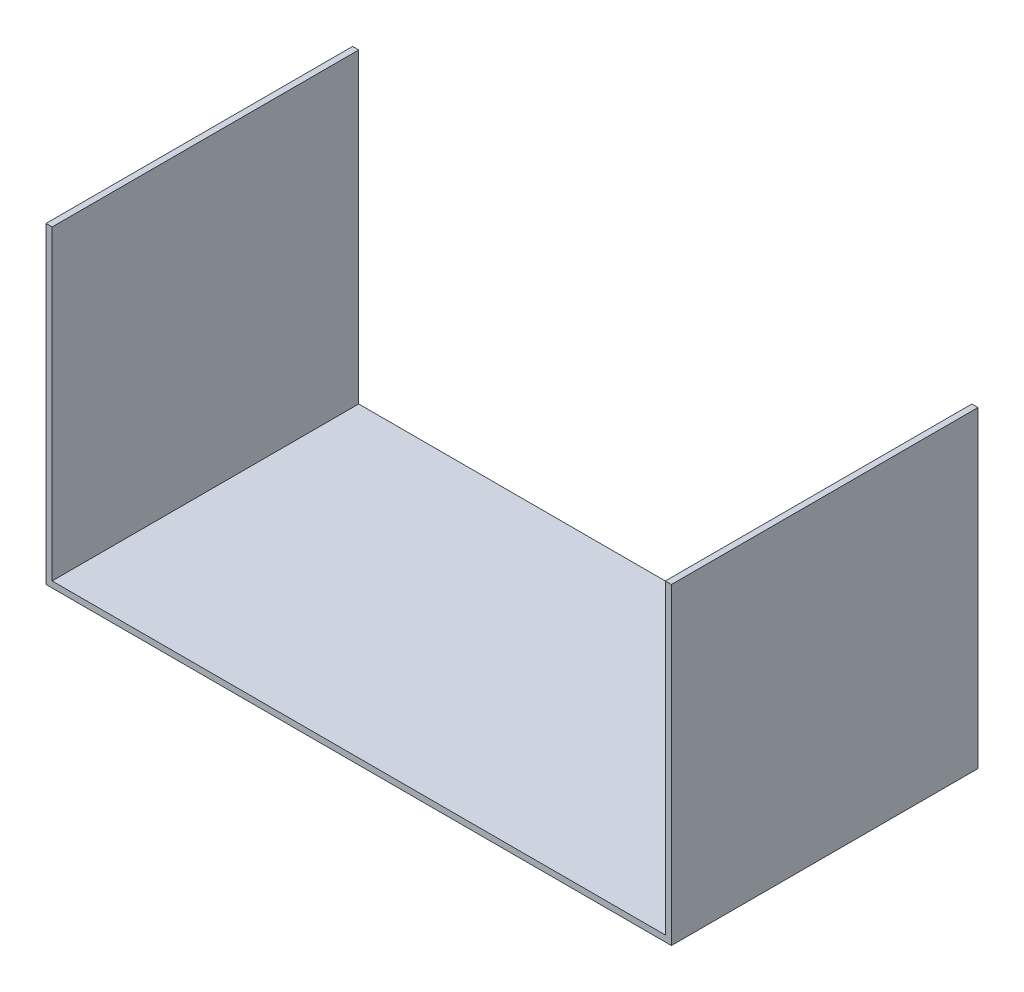
SolidWorks part; units mm, degrees
ref_plane "Front Plane" through (0, 0, 0) normal (0, 0, 1) x (1, 0, 0)
ref_plane "Top Plane" through (0, 0, 0) normal (0, 1, 0) x (1, 0, 0)
ref_plane "Right Plane" through (0, 0, 0) normal (1, 0, 0) x (0, 0, -1)
sketch "Sketch2" plane through (0, 0, 0) normal (0, 0, 1) x (1, 0, 0)
  line L0 (0, 0) -> (0, -10000)
  line L1 (0, -10000) -> (20000, -10000)
  line L2 (20000, -10000) -> (20000, 0)
  line L3 (-200, 0) -> (-200, -10200)
  line L4 (-200, -10200) -> (20200, -10200)
  line L5 (20200, -10200) -> (20200, 0)
  line L6 (-200, 0) -> (0, 0)
  line L7 (20000, 0) -> (20200, 0)
extrude "Boss-Extrude1" add sketch "Sketch2" along normal blind 10000
